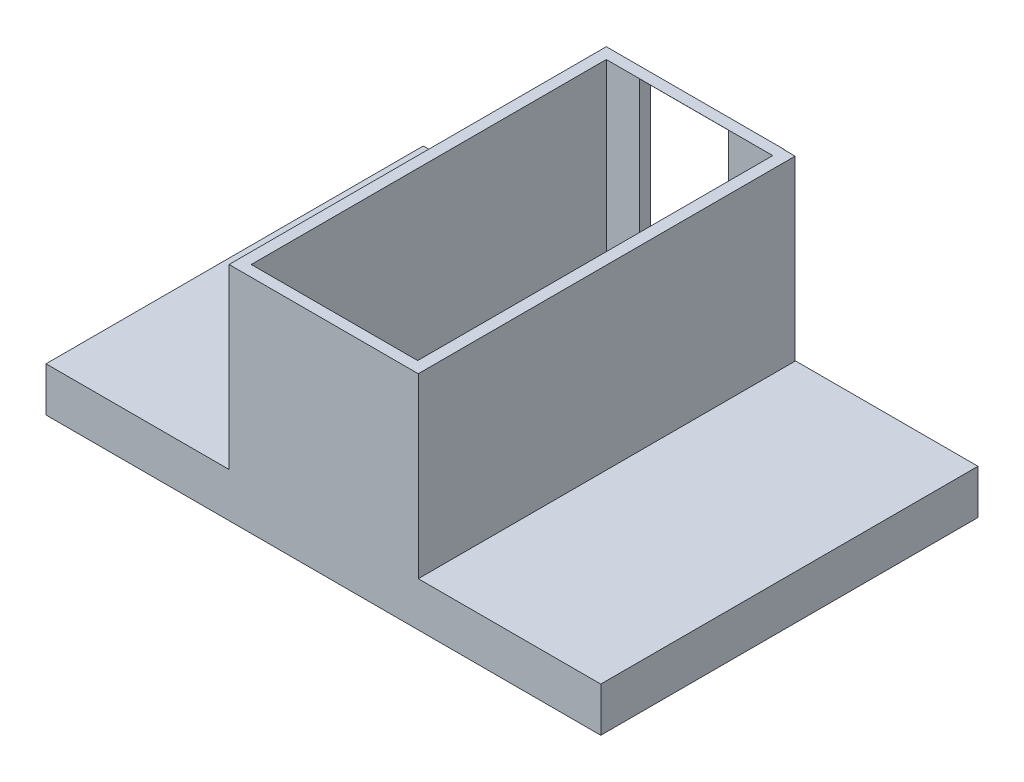
SolidWorks part; units mm, degrees
ref_plane "Front Plane" through (0, 0, 0) normal (0, 0, 1) x (1, 0, 0)
ref_plane "Top Plane" through (0, 0, 0) normal (0, 1, 0) x (1, 0, 0)
ref_plane "Right Plane" through (0, 0, 0) normal (1, 0, 0) x (0, 0, -1)
sketch "Sketch1" plane through (0, 0, 0) normal (0, 1, 0) x (1, 0, 0)
  line L0 (-60.7292, -26.4383) -> (2.7708, -26.4383)
  line L1 (-60.7292, -26.4383) -> (-60.7292, -4.8483)
  line L2 (2.7708, -26.4383) -> (2.7708, -4.8483)
  line L3 (-60.7292, -4.8483) -> (2.7708, -4.8483)
  dimension "D1" = 63.5
  dimension "D2" = 21.59
extrude "Boss-Extrude1" add sketch "Sketch1" along normal blind 5.08
sketch "Sketch2" plane through (0, 0, 26.4383) normal (0, 0, 1) x (1, 0, 0)
  line L0 (-38.5042, 5.08) -> (-19.4542, 5.08)
  line L1 (-38.5042, 5.08) -> (-38.5042, 25.4)
  line L2 (-19.4542, 5.08) -> (-19.4542, 25.4)
  line L3 (-38.5042, 25.4) -> (-19.4542, 25.4)
  line L4 (-60.7292, 5.08) -> (2.7708, 5.08) construction
  dimension "D1" = 19.05
  dimension "D2" = 22.225
  dimension "D3" = 20.32
extrude "Boss-Extrude2" add sketch "Sketch2" against normal blind 1.27
sketch "Sketch3" plane through (0, 5.08, 0) normal (0, 1, 0) x (1, 0, 0)
  line L0 (-38.5042, -26.4383) -> (-39.7742, -26.4383)
  line L1 (-38.5042, -26.4383) -> (-38.5042, -4.8483)
  line L2 (-39.7742, -26.4383) -> (-39.7742, -4.8483)
  line L3 (-38.5042, -4.8483) -> (-39.7742, -4.8483)
  line L4 (-60.7292, -26.4383) -> (-38.5042, -26.4383) construction
  dimension "D1" = 21.59
  dimension "D2" = 1.27
extrude "Boss-Extrude3" add sketch "Sketch3" along normal blind 20.32
mirror "Mirror2" about plane through (-60.7292, 5.08, 4.8483) normal (0, 0, 1) of "Boss-Extrude1", "Boss-Extrude2", "Boss-Extrude3"
sketch "Sketch4" plane through (0, 5.08, 0) normal (0, 1, 0) x (1, 0, 0)
  line L0 (-19.4542, -26.4383) -> (-18.1182, -26.4383)
  line L1 (-19.4542, -26.4383) -> (-19.4542, 16.6983)
  line L2 (-18.1182, -26.4383) -> (-18.1182, 16.6983)
  line L3 (-19.4542, 16.6983) -> (-18.1182, 16.6983)
  line L4 (-19.4542, -26.4383) -> (2.7708, -26.4383) construction
extrude "Boss-Extrude4" add sketch "Sketch4" along normal blind 20.32
sketch "Sketch5" plane through (0, 0, -16.7417) normal (0, 0, -1) x (-1, 0, 0)
  line L0 (24.5334, 5.1719) -> (34.6934, 5.1719)
  line L1 (24.5334, 5.1719) -> (24.5334, 25.3871)
  line L2 (34.6934, 5.1719) -> (34.6934, 25.3871)
  line L3 (24.5334, 25.3871) -> (34.6934, 25.3871)
  dimension "D1" = 10.16
  dimension "D2" = 5.08
extrude "Cut-Extrude2" cut sketch "Sketch5" against normal blind 1.27
